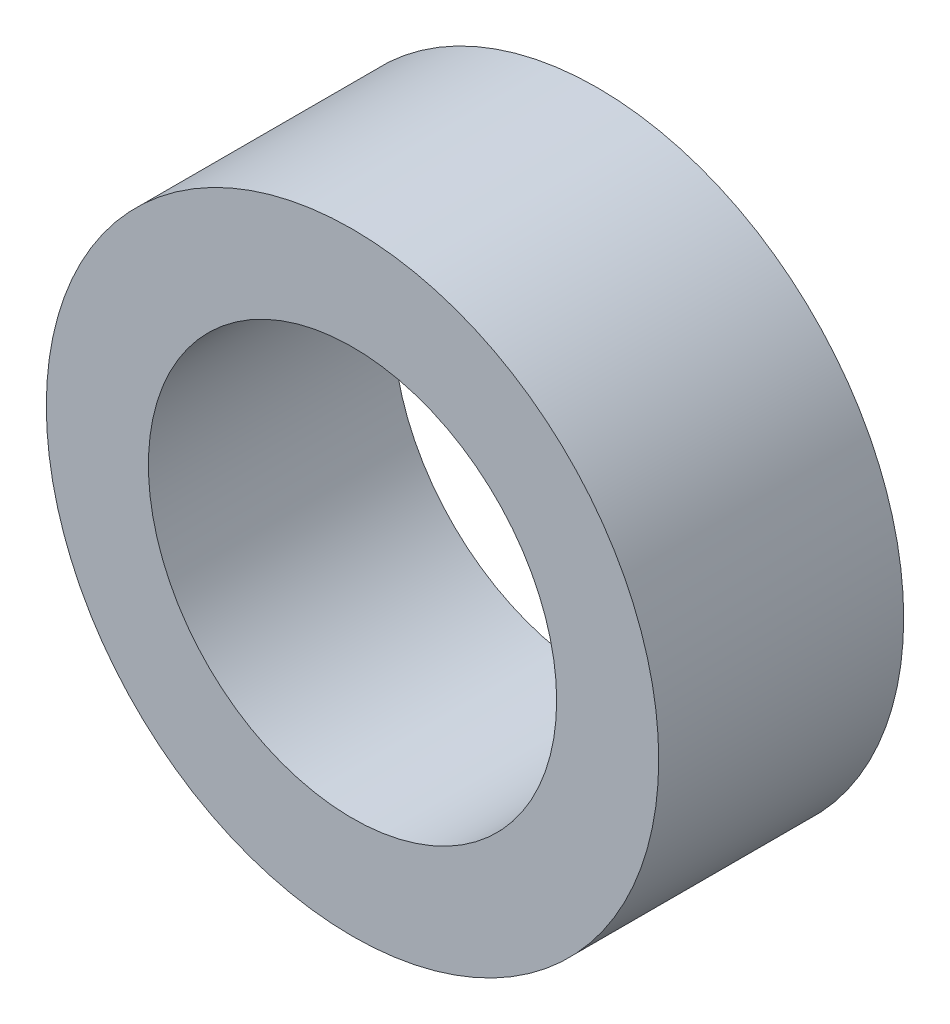
SolidWorks part; units mm, degrees
material "Náilon 101"
ref_plane "Plano frontal" through (0, 0, 0) normal (0, 0, 1) x (1, 0, 0)
ref_plane "Plano superior" through (0, 0, 0) normal (0, 1, 0) x (1, 0, 0)
ref_plane "Plano direito" through (0, 0, 0) normal (1, 0, 0) x (0, 0, -1)
sketch "Esboço1" plane through (0, 0, 0) normal (0, 0, 1) x (1, 0, 0)
  circle A0 centre (0, 0) radius 3.75
  circle A1 centre (0, 0) radius 2.5
  dimension "D1" = 7.5
  dimension "D2" = 5
extrude "Ressalto-extrusão1" add sketch "Esboço1" along normal mid plane 3
